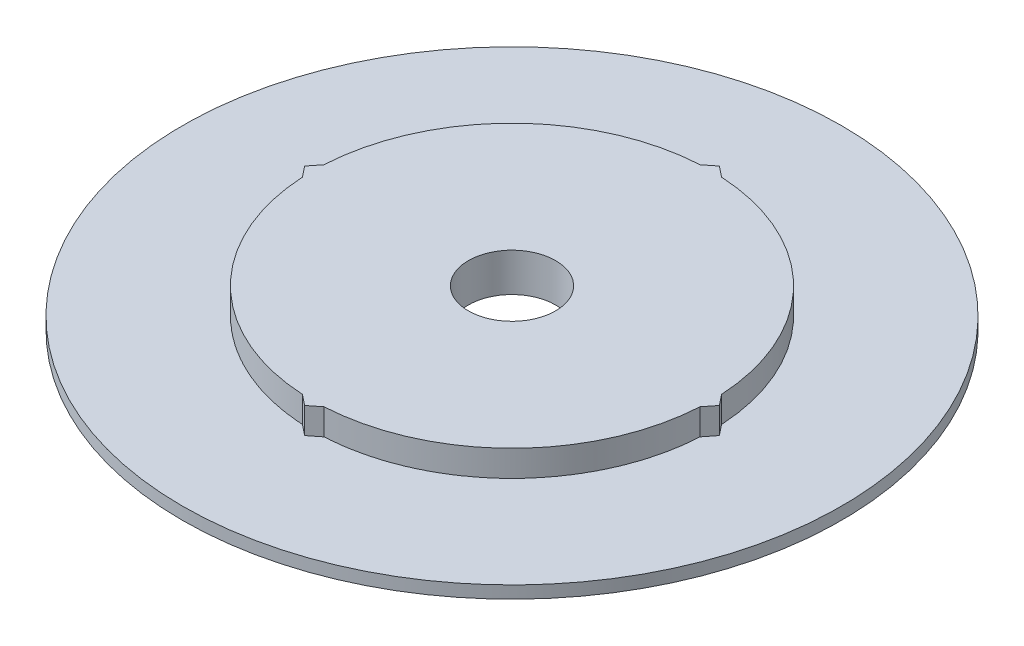
SolidWorks part; units mm, degrees
ref_plane "Front Plane" through (0, 0, 0) normal (0, 0, 1) x (1, 0, 0)
ref_plane "Top Plane" through (0, 0, 0) normal (0, 1, 0) x (1, 0, 0)
ref_plane "Right Plane" through (0, 0, 0) normal (1, 0, 0) x (0, 0, -1)
sketch "Sketch1" plane through (0, 0, 0) normal (0, 1, 0) x (1, 0, 0)
  circle A0 centre (0, 0) radius 14.5
  circle A1 centre (0, 0) radius 24
  dimension "D1" = 48
  dimension "D2" = 29
extrude "Boss-Extrude1" add sketch "Sketch1" along normal blind 0.9
sketch "Sketch2" plane through (0, 0, 0) normal (0, -1, 0) x (1, 0, 0)
  circle A0 centre (0, 0) radius 14.5 construction
  circle A1 centre (0, 0) radius 14.5
  circle A2 centre (0, 0) radius 3.175
  dimension "D1" = 6.35
extrude "Boss-Extrude2" add sketch "Sketch2" against normal blind 2.8 separate body
sketch "Sketch3" plane through (0, 2.8, 0) normal (0, 1, 0) x (1, 0, 0)
  line L0 (-14.5, 0) -> (-15.1, 0) construction
  line L1 (-15.1, 0) -> (-14.4788, 0.7837)
  line L2 (-15.1, 0) -> (-14.4788, -0.7837)
  line L3 (0, 15.1) -> (0.7837, 14.4788)
  line L4 (0, 15.1) -> (-0.7837, 14.4788)
  line L5 (0, 14.5) -> (0, 15.1) construction
  line L6 (15.1, 0) -> (14.4788, -0.7837)
  line L7 (15.1, 0) -> (14.4788, 0.7837)
  line L8 (14.5, 0) -> (15.1, 0) construction
  line L9 (0, -15.1) -> (-0.7837, -14.4788)
  line L10 (0, -15.1) -> (0.7837, -14.4788)
  line L11 (0, -14.5) -> (0, -15.1) construction
  circle A0 centre (0, 0) radius 14.5 construction
  arc A1 (-14.4788, 0.7837) -> (-14.4788, -0.7837) centre (0, 0) ccw
  arc A2 (0.7837, 14.4788) -> (-0.7837, 14.4788) centre (0, 0) ccw
  arc A3 (14.4788, -0.7837) -> (14.4788, 0.7837) centre (0, 0) ccw
  arc A4 (-0.7837, -14.4788) -> (0.7837, -14.4788) centre (0, 0) ccw
  point P22 (0, 0)
  dimension "D1" = 1
  dimension "D2" = 1
  dimension "D3" = 0.6
  dimension "D4" = 4
extrude "Boss-Extrude3" add sketch "Sketch3" against normal up to surface (2.8 mm away) up to face at (0, 0, -3.175)
